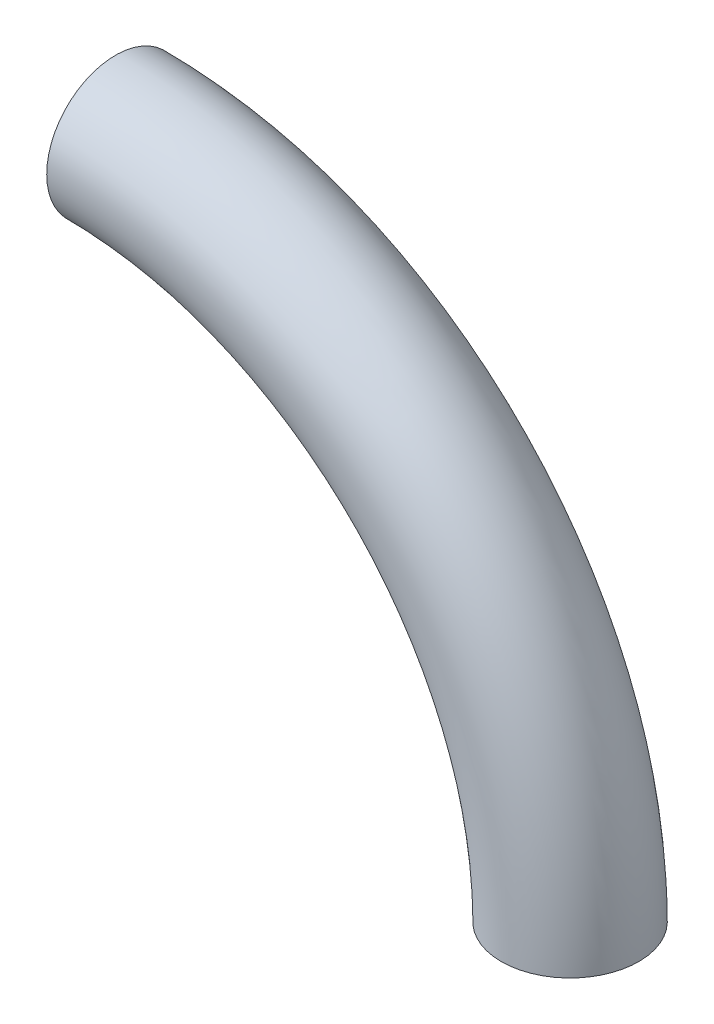
SolidWorks part; units mm, degrees
ref_plane "Front Plane" through (0, 0, 0) normal (0, 0, 1) x (1, 0, 0)
ref_plane "Top Plane" through (0, 0, 0) normal (0, 1, 0) x (1, 0, 0)
ref_plane "Right Plane" through (0, 0, 0) normal (1, 0, 0) x (0, 0, -1)
sketch "Sketch5" plane through (0, 0, 0) normal (0, 0, 1) x (1, 0, 0)
  arc A0 (0, 50.5709) -> (50.5709, 0) centre (0, 0) cw
sketch "Sketch6" plane through (0, 0, 0) normal (0, 1, 0) x (1, 0, 0)
  circle A0 centre (50.5709, 0) radius 7.6505
sweep "Sweep2" add profiles "Sketch6" path "Sketch5"
